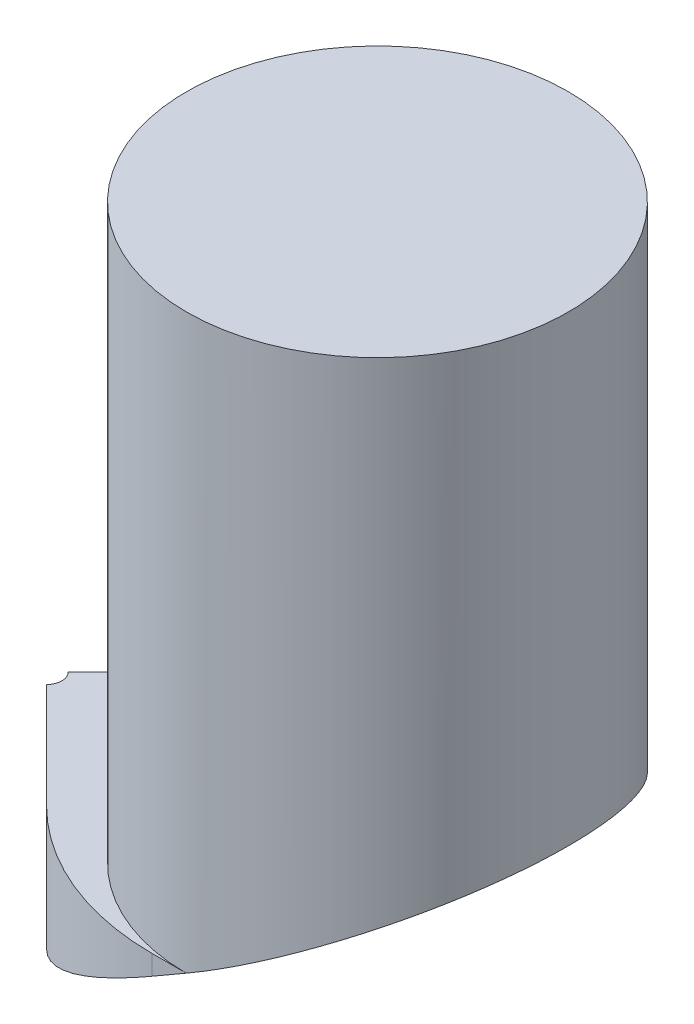
SolidWorks part; units mm, degrees
ref_plane "Front Plane" through (0, 0, 0) normal (0, 0, 1) x (1, 0, 0)
ref_plane "Top Plane" through (0, 0, 0) normal (0, 1, 0) x (1, 0, 0)
ref_plane "Right Plane" through (0, 0, 0) normal (1, 0, 0) x (0, 0, -1)
sketch "Sketch1" plane through (0, 0, 0) normal (0, 1, 0) x (1, 0, 0)
  line L0 (-55, 0) -> (55, 0) construction
  line L1 (0, 0) -> (323.9878, 323.9878) construction
  line L2 (0, 0) -> (323.9878, -323.9878) construction
  line L3 (8.4853, -8.4853) -> (150, -150)
  line L4 (150, -150) -> (260, -150)
  line L5 (150, 150) -> (260, 150)
  line L6 (8.4853, 8.4853) -> (150, 150)
  arc A0 (8.4853, -8.4853) -> (8.4853, 8.4853) centre (0, 0) ccw
  circle A1 centre (0, 0) radius 12 construction
  circle A2 centre (0, 0) radius 110 construction
  arc A3 (260, -150) -> (260, 150) centre (260, 0) ccw
  dimension "D1" = 24
  dimension "D2" = 24
  dimension "D3" = 220
  dimension "D4" = 300
  dimension "D5" = 45
extrude "Boss-Extrude1" add sketch "Sketch1" along normal blind 600
sketch "Sketch2" plane through (0, 0, 0) normal (0, 0, 1) x (1, 0, 0)
  line L0 (0, 0) -> (410, 236.7136)
  line L1 (410, 236.7136) -> (410, 0)
  line L2 (410, 0) -> (0, 0)
  line L3 (260, 0) -> (410, 0) construction
  line L4 (55, 0) -> (-55, 0) construction
  dimension "D1" = 30
extrude "Cut-Extrude1" cut sketch "Sketch2" against normal through all both and the other way through all
sketch "Sketch3" plane through (0, 600, 0) normal (0, 1, 0) x (1, 0, 0)
  line L0 (0, 0) -> (150, 150)
  line L1 (0, 0) -> (150, -150)
  line L2 (150, -150) -> (260, -150)
  line L4 (-55, 0) -> (55, 0) construction
  line L5 (150, 150) -> (260, 150)
  arc A0 (260, 150) -> (260, -150) centre (260, 0) ccw
extrude "Cut-Extrude2" cut sketch "Sketch3" along direction (0, 1, 0) on the side against the normal blind 450
fillet "Fillet1" radius 200 2 edges at (150, 118.3013, 150) (150, 118.3013, -150)
sketch "Sketch4" plane through (0, 0, 0) normal (1, 0, 0) x (0, 0, -1)
  line L0 (16.7572, 600) -> (16.7572, 150)
  line L1 (150, 600) -> (-150, 600) construction
  line L2 (149.9999, 150) -> (-149.9999, 150) construction
  point P2 (0, 0)
  point P5 (0, 0)
